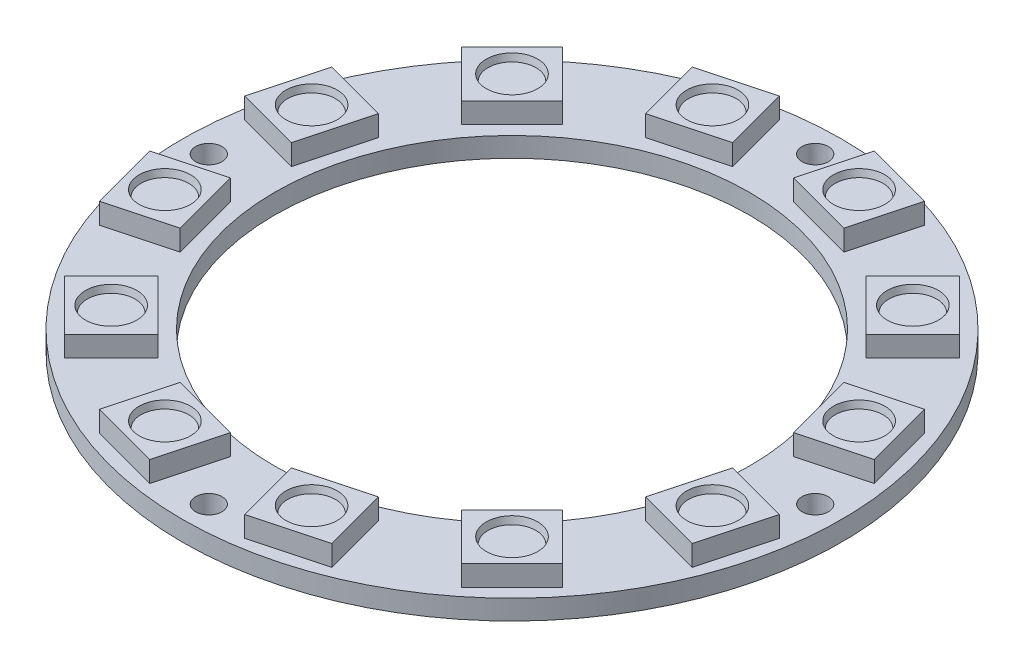
SolidWorks part; units mm, degrees
ref_plane "Plan de face" through (0, 0, 0) normal (0, 0, 1) x (1, 0, 0)
ref_plane "Plan de dessus" through (0, 0, 0) normal (0, 1, 0) x (1, 0, 0)
ref_plane "Plan de droite" through (0, 0, 0) normal (1, 0, 0) x (0, 0, -1)
ref_axis "Axe1" through (0, 2.4752, 0) along (0, -1, 0)
sketch "Contour" plane through (0, 0, 0) normal (0, 0, 1) x (1, 0, 0)
  line L0 (27.5, 0) -> (-27.5, 0) construction
  line L1 (18, -0.75) -> (25, -0.75)
  line L2 (18, -0.75) -> (18, 0.75)
  line L3 (18, 0.75) -> (25, 0.75)
  line L4 (25, -0.75) -> (25, 0.75)
  line L5 (18, -0.75) -> (25, 0.75) construction
  line L6 (18, 0.75) -> (25, -0.75) construction
  line L7 (0, -1.7076) -> (0, 1.7076) construction
  point P0 (21.5, 0)
  dimension "D1" = 7
  dimension "D2" = 1.5
  dimension "D3" = 18
revolve "Révolution1_Contour" add sketch "Contour" angle 360 about axis through (0, 2.4752, 0) along (0, -1, 0)
sketch "RGB_DEL" plane through (0, 0.75, 0) normal (0, 1, 0) x (1, 0, 0)
  line L0 (-13.435, 13.435) -> (0, 0) construction
  line L11 (-15.3442, 11.5258) -> (-11.5258, 15.3442)
  line L12 (-11.5258, 15.3442) -> (-15.0614, 18.8798)
  line L13 (-15.0614, 18.8798) -> (-18.8798, 15.0614)
  line L14 (-18.8798, 15.0614) -> (-15.3442, 11.5258)
  line L15 (0, 0) -> (25, 0) construction
  circle A0 centre (0, 0) radius 25 construction
  dimension "D3" = 19
  dimension "D4" = 5
  dimension "D5" = 5.4
  dimension "D6" = 135
extrude "Boss.-Extru.2_RGB_DEL" add sketch "RGB_DEL" along normal blind 1.57
pattern_circular "Répétition circulaire1_RGB_DEL" count 12 over 360 about axis through (0, 0, 0) along (0, 1, 0) of "Boss.-Extru.2_RGB_DEL"
sketch "Beignets_soudures" plane through (0, -0.75, 0) normal (0, -1, 0) x (-1, 0, 0)
  line L0 (12.5087, 17.8969) -> (14.3048, 16.1008) construction
  line L5 (8.1317, 18.7383) -> (18.7383, 8.1317) construction
  line L11 (18.7383, 8.1317) -> (22.2739, 11.6673) construction
  line L12 (22.2739, 11.6673) -> (11.6673, 22.2739) construction
  line L17 (11.6673, 22.2739) -> (8.1317, 18.7383) construction
  line L23 (11.6673, 22.2739) -> (18.7383, 8.1317) construction
  line L26 (8.1317, 18.7383) -> (22.2739, 11.6673) construction
  line L27 (14.3048, 16.1008) -> (16.1008, 14.3048) construction
  line L28 (16.1008, 14.3048) -> (17.8969, 12.5087) construction
  line L29 (15.2028, 15.2028) -> (0, 0) construction
  line L30 (0, 0) -> (25, 0) construction
  circle A7 centre (12.5087, 17.8969) radius 0.875
  circle A8 centre (14.3048, 16.1008) radius 0.875
  circle A9 centre (16.1008, 14.3048) radius 0.875
  circle A10 centre (17.8969, 12.5087) radius 0.875
  circle A11 centre (0, 0) radius 25 construction
  point P2 (15.2028, 15.2028)
  dimension "D1" = 15
  dimension "D4" = 1.75
  dimension "D5" = 2.54
  dimension "D2" = 5
  dimension "D6" = 21.5
  dimension "D7" = 45
extrude "Boss.-Extru.3_Beignets_soudures" add sketch "Beignets_soudures" along normal blind 0.0348
sketch "Alignement" plane through (0, -0.75, 0) normal (0, -1, 0) x (-1, 0, 0)
  line L3 (12.5087, 17.8969) -> (17.8969, 12.5087) construction
  circle A0 centre (15.2028, 15.2028) radius 2.7 construction
  point P1 (15.2028, 15.2028)
  dimension "D1" = 5.4
sketch "Lentille" plane through (0, 2.32, 0) normal (0, 1, 0) x (1, 0, 0)
  line L0 (-15.0614, 18.8798) -> (-15.3442, 11.5258) construction
  line L1 (-18.8798, 15.0614) -> (-11.5258, 15.3442) construction
  line L2 (-11.5258, 15.3442) -> (-15.0614, 18.8798) construction
  line L3 (-15.3442, 11.5258) -> (-11.5258, 15.3442) construction
  circle A0 centre (-15.2028, 15.2028) radius 1.95
  point P18 (-15.2028, 15.2028)
  dimension "D1" = 3.9
extrude "Enlèv. mat.-Extru.1_Lentille" cut sketch "Lentille" against normal blind 0.5 draft 15
pattern_circular "Répétition circulaire1" count 12 over 360 about axis through (0, 0, 0) along (0, 1, 0) of "Enlèv. mat.-Extru.1_Lentille"
sketch "Tous_Montage_Vis_M2_Anneau_RGB" plane through (0, 0, 0) normal (0, 1, 0) x (1, 0, 0)
  line L0 (0, -23) -> (0, 23) construction
  line L1 (-23, 0) -> (23, 0) construction
  line L2 (-1.7076, 0) -> (1.7076, 0) construction
  circle A0 centre (-23, 0) radius 1
  circle A1 centre (0, 23) radius 1
  circle A2 centre (23, 0) radius 1
  circle A3 centre (0, -23) radius 1
  point P2 (0, 0)
  point P6 (0, 0)
  dimension "D3" = 2
  dimension "D1" = 46
  dimension "D2" = 90
extrude "Enlèv. mat.-Extru.1_Tous_Montage_Vis_M2_Anneau_RGB" cut sketch "Tous_Montage_Vis_M2_Anneau_RGB" against normal mid plane 5
equation "\"D3@Contour\"=36 / 2"
